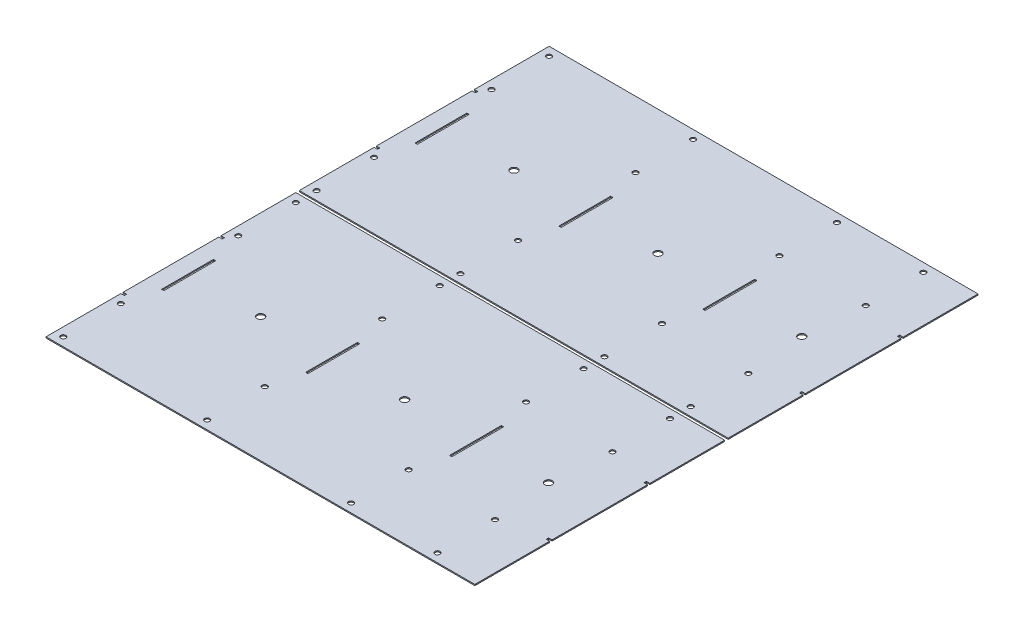
SolidWorks part; units mm, degrees
ref_plane "Front Plane" through (0, 0, 0) normal (0, 0, 1) x (1, 0, 0)
ref_plane "Top Plane" through (0, 0, 0) normal (0, 1, 0) x (1, 0, 0)
ref_plane "Right Plane" through (0, 0, 0) normal (1, 0, 0) x (0, 0, -1)
sketch "Sketch1" plane through (0, 0, 0) normal (0, 1, 0) x (1, 0, 0)
  line L0 (-8, 41.5) -> (-8, -41.5) construction
  line L1 (-8, 0) -> (0, 0) construction
  line L2 (-8, -41.5) -> (-8, -43.5) construction
  line L3 (-8, -43.5) -> (-8, -51) construction
  line L4 (-8, -51) -> (-8, -101) construction
  line L5 (0, 0) -> (125, 0) construction
  line L6 (-8, 41.5) -> (-8, 43.5) construction
  line L7 (-8, 43.5) -> (-8, 51) construction
  line L8 (-8, 51) -> (-8, 101) construction
  line L9 (117, -51) -> (117, -101) construction
  line L10 (117, -43.5) -> (117, -51) construction
  line L11 (117, -41.5) -> (117, -43.5) construction
  line L12 (117, 41.5) -> (117, -41.5) construction
  line L13 (117, 0) -> (125, 0) construction
  line L14 (124, -22.5) -> (126, -22.5)
  line L15 (-1, 22.5) -> (1, 22.5)
  line L16 (-1, 22.5) -> (-1, -22.5)
  line L17 (-1, -22.5) -> (1, -22.5)
  line L18 (1, 22.5) -> (1, -22.5)
  line L19 (-1, 22.5) -> (1, -22.5) construction
  line L20 (-1, -22.5) -> (1, 22.5) construction
  line L21 (124, 22.5) -> (124, -22.5)
  line L22 (124, -22.5) -> (126, 22.5) construction
  line L23 (124, 22.5) -> (126, -22.5) construction
  line L24 (126, 22.5) -> (126, -22.5)
  line L25 (124, 22.5) -> (126, 22.5)
  line L26 (117, 41.5) -> (117, 43.5) construction
  line L27 (117, 43.5) -> (117, 51) construction
  line L28 (117, 51) -> (117, 101) construction
  line L29 (242, -51) -> (242, -101) construction
  line L30 (242, -43.5) -> (242, -51) construction
  line L31 (242, -41.5) -> (242, -43.5) construction
  line L32 (242, 41.5) -> (242, -41.5) construction
  line L33 (242, 0) -> (250, 0) construction
  line L34 (249, -22.5) -> (251, -22.5)
  line L35 (249, 22.5) -> (249, -22.5)
  line L36 (249, -22.5) -> (251, 22.5) construction
  line L37 (249, 22.5) -> (251, -22.5) construction
  line L38 (251, 22.5) -> (251, -22.5)
  line L39 (249, 22.5) -> (251, 22.5)
  line L40 (242, 41.5) -> (242, 43.5) construction
  line L41 (242, 43.5) -> (242, 51) construction
  line L42 (242, 51) -> (242, 101) construction
  line L43 (367, 108.5) -> (367, -108.5) construction
  line L44 (357, 108.5) -> (367, 108.5) construction
  line L45 (357, -108.5) -> (367, -108.5) construction
  line L46 (317, 108.5) -> (317, -108.5) construction
  line L57 (-15.5, -108.5) -> (357, -108.5)
  line L58 (357, -108.5) -> (357, -43.5)
  line L59 (357, -43.5) -> (354, -43.5)
  line L60 (354, -43.5) -> (354, -41.5)
  line L61 (354, -41.5) -> (357, -41.5)
  line L62 (357, -41.5) -> (357, 41.5)
  line L63 (357, 41.5) -> (354, 41.5)
  line L64 (354, 41.5) -> (354, 43.5)
  line L65 (354, 43.5) -> (357, 43.5)
  line L66 (357, 43.5) -> (357, 108.5)
  line L67 (357, 108.5) -> (-15.5, 108.5)
  line L68 (-15.5, 108.5) -> (-15.5, 43.5)
  line L69 (-15.5, 43.5) -> (-12.5, 43.5)
  line L70 (-12.5, 43.5) -> (-12.5, 41.5)
  line L71 (-12.5, 41.5) -> (-15.5, 41.5)
  line L72 (-15.5, 41.5) -> (-15.5, -41.5)
  line L73 (-15.5, -41.5) -> (-12.5, -41.5)
  line L74 (-12.5, -41.5) -> (-12.5, -43.5)
  line L75 (-12.5, -43.5) -> (-15.5, -43.5)
  line L76 (-15.5, -43.5) -> (-15.5, -108.5)
  line L78 (-15.5, 0) -> (-8, 0) construction
  line L79 (-12.5, -41.5) -> (-8, -41.5) construction
  line L80 (354, 43.5) -> (-12.5, 43.5) construction
  line L81 (-12.5, 41.5) -> (354, 41.5) construction
  line L82 (354, -41.5) -> (-12.5, -41.5) construction
  line L83 (-12.5, -43.5) -> (354, -43.5) construction
  circle A0 centre (-8, -101) radius 2.2
  circle A1 centre (-8, -51) radius 2.2
  circle A2 centre (-8, 51) radius 2.2
  circle A3 centre (-8, 101) radius 2.2
  circle A4 centre (117, -101) radius 2.2
  circle A5 centre (117, -51) radius 2.2
  circle A6 centre (117, 51) radius 2.2
  circle A7 centre (117, 101) radius 2.2
  circle A8 centre (242, -101) radius 2.2
  circle A9 centre (242, -51) radius 2.2
  circle A10 centre (242, 51) radius 2.2
  circle A11 centre (242, 101) radius 2.2
  circle A16 centre (62.5, 0) radius 3.175
  circle A17 centre (187.5, 0) radius 3.175
  circle A18 centre (312.5, 0) radius 3.175
  circle A45 centre (367, 101) radius 2.2 construction
  circle A46 centre (367, -101) radius 2.2 construction
  circle A47 centre (317, 101) radius 2.2
  circle A48 centre (317, 51) radius 2.2
  circle A49 centre (317, -101) radius 2.2
  circle A50 centre (317, -51) radius 2.2
  point P14 (0, 0)
  dimension "D1" = 83
  dimension "D2" = 4.4
  dimension "D18" = 6.35
  dimension "D19" = 7.5
  dimension "D14" = 7.5
  dimension "D22" = 7.5
  dimension "D27" = 4.4
  dimension "D3" = 8
  dimension "D4" = 45
  dimension "D5" = 2
  dimension "D6" = 50
  dimension "D7" = 2
  dimension "D8" = 7.5
  dimension "D9" = 125
  dimension "D11" = 125
  dimension "D12" = 7.5
  dimension "D13" = 3
  dimension "D15" = 3
  dimension "D16" = 7.5
  dimension "D17" = 7.5
  dimension "D20" = 125
  dimension "D21" = 40
  dimension "D23" = 50
  dimension "D24" = 50
  dimension "D25" = 7.5
  dimension "D26" = 50
  dimension "D10" = 3
extrude "Boss-Extrude1" add sketch "Sketch1" along normal blind 1
pattern_linear "LPattern1" count 2 spacing 220 along (0, 0, -1) of bodies 101
